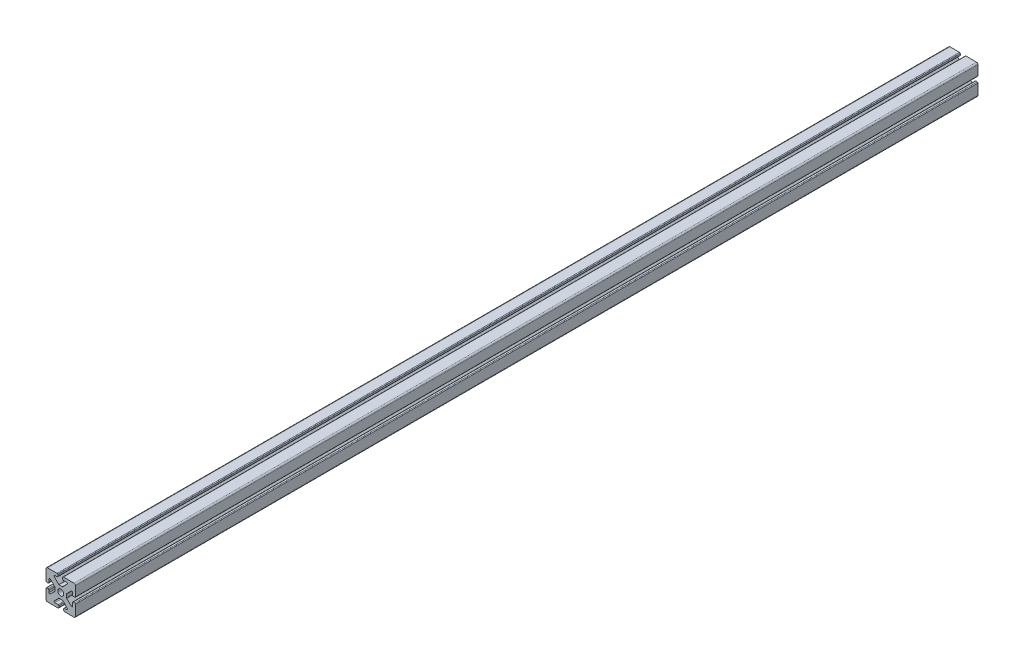
SolidWorks part; units mm, degrees
ref_plane "Front" through (0, 0, 0) normal (0, 0, 1) x (1, 0, 0)
ref_plane "Top" through (0, 0, 0) normal (0, 1, 0) x (1, 0, 0)
ref_plane "Right" through (0, 0, 0) normal (1, 0, 0) x (0, 0, -1)
sketch "草图1" plane through (0, 0, 0) normal (0, 0, 1) x (1, 0, 0)
  line L1 (-20, 20) -> (20, 20)
  line L2 (-20, 20) -> (-20, -20)
  line L3 (-20, -20) -> (20, -20)
  line L4 (20, 20) -> (20, -20)
  line L5 (-20, 20) -> (20, -20) construction
  line L6 (-20, -20) -> (20, 20) construction
  point P0 (0, 0)
  dimension "D1" = 40
extrude "凸台-拉伸1" add sketch "草图1" along normal blind 1223
sketch "草图2" plane through (0, 0, 1223) normal (0, 0, 1) x (1, 0, 0)
  circle A0 centre (0, 0) radius 4.05
  dimension "D1" = 8.1
extrude "切除-拉伸1" cut sketch "草图2" against normal blind 10000
sketch "草图4" plane through (0, 0, 1223) normal (0, 0, 1) x (1, 0, 0)
  line L0 (20, -20) -> (20, 20) construction
  line L1 (20, 0) -> (20, 4)
  line L2 (20, 0) -> (20, -2.652)
  line L3 (7.8769, 2.6) -> (7.8769, -2.6)
  line L4 (20, 4) -> (16, 4)
  line L5 (20, -2.652) -> (16, -2.652)
  line L6 (16, 10.5) -> (16, 4)
  line L7 (16, 10.5) -> (7.8769, 2.6)
  line L8 (16, -10.5) -> (7.8769, -2.6)
  line L9 (16, -2.652) -> (16, -10.5)
  point P11 (7.8769, 0)
  point P12 (16, 0)
extrude "切除-拉伸2" cut sketch "草图4" against normal blind 10000
fillet "圆角1" radius 1 8 edges at (16, 10.5, 611.5) (16, -10.5, 611.5) (7.8769, 2.6, 611.5) (20, -2.652, 611.5) (16, -2.652, 611.5) (20, 4, 611.5) (16, 4, 611.5) (7.8769, -2.6, 611.5)
pattern_circular "阵列(圆周)2" count 4 over 360 about axis through (0, 0, 0) along (0, 0, 1) of "切除-拉伸2"
fillet "圆角2" radius 1 8 edges at (10.5, 16, 611.5) (-10.5, 16, 611.5) (-4, 20, 611.5) (2.652, 16, 611.5) (2.652, 20, 611.5) (-2.6, 7.8769, 611.5) (-4, 16, 611.5) (2.6, 7.8769, 611.5)
fillet "圆角3" radius 1 8 edges at (-7.8769, -2.6, 611.5) (-7.8769, 2.6, 611.5) (-20, 2.652, 611.5) (-16, 10.5, 611.5) (-20, -4, 611.5) (-16, -4, 611.5) (-16, -10.5, 611.5) (-16, 2.652, 611.5)
fillet "圆角4" radius 1 8 edges at (4, -20, 611.5) (4, -16, 611.5) (10.5, -16, 611.5) (-2.652, -20, 611.5) (2.6, -7.8769, 611.5) (-2.6, -7.8769, 611.5) (-2.652, -16, 611.5) (-10.5, -16, 611.5)
fillet "圆角5" radius 2 4 edges at (-20, -20, 611.5) (20, -20, 611.5) (-20, 20, 611.5) (20, 20, 611.5)
